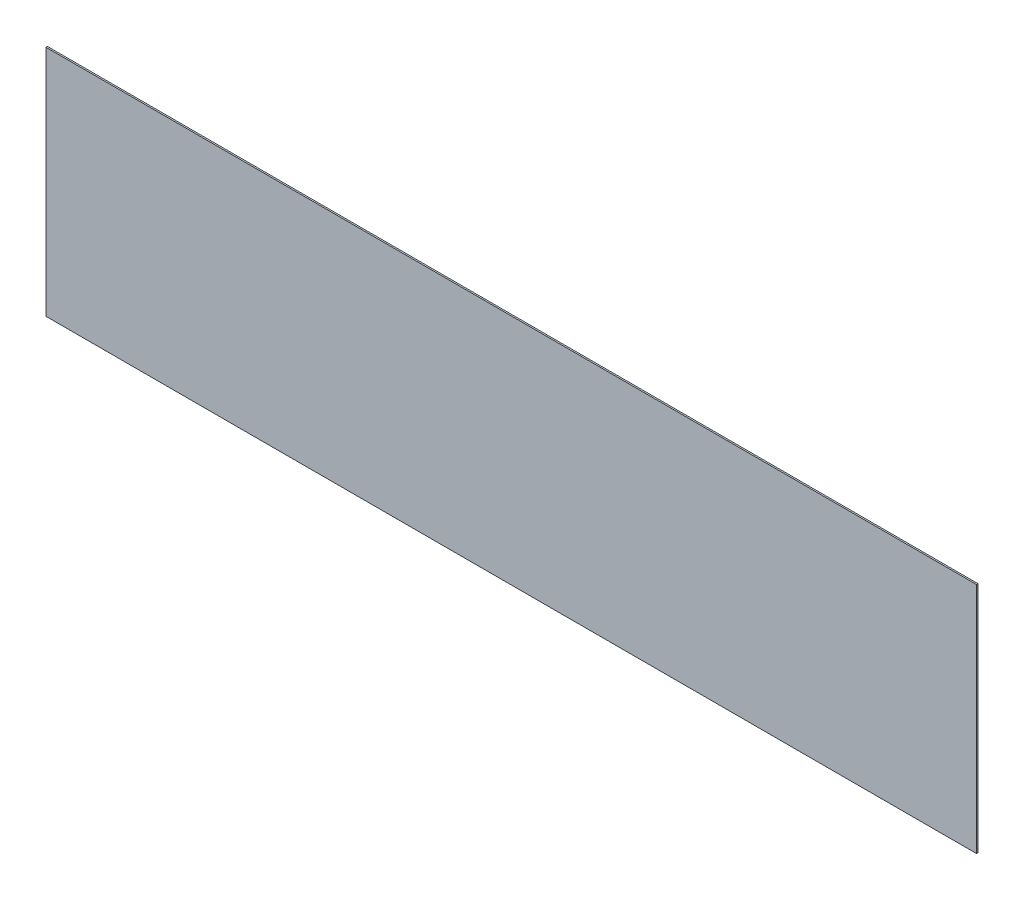
SolidWorks part; units mm, degrees
ref_plane "Front Plane" through (0, 0, 0) normal (0, 0, 1) x (1, 0, 0)
ref_plane "Top Plane" through (0, 0, 0) normal (0, 1, 0) x (1, 0, 0)
ref_plane "Right Plane" through (0, 0, 0) normal (1, 0, 0) x (0, 0, -1)
sketch "Sketch1" plane through (0, 0, 0) normal (0, 0, 1) x (1, 0, 0)
  line L0 (1242, 311) -> (1242, 0)
  line L1 (1242, 311) -> (0, 311)
  line L2 (1242, 0) -> (0, 0)
  line L3 (0, 311) -> (0, 0)
other "Pen Sketch1" parameters "D1"=69.7562, "D2"=44.2015
extrude "Boss-Extrude1" add sketch "Sketch1" along normal blind 2
